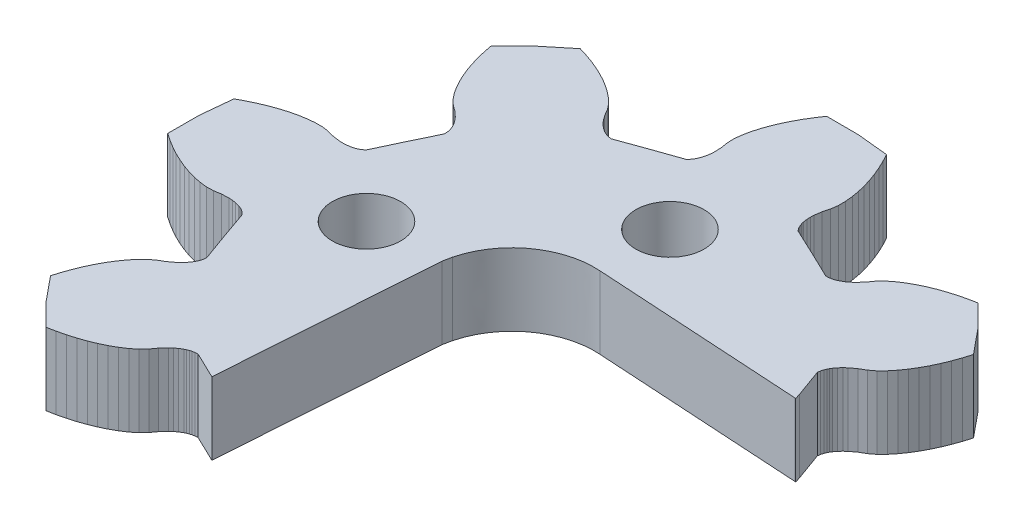
SolidWorks part; units mm, degrees
ref_plane "Front Plane" through (0, 0, 0) normal (0, 0, 1) x (1, 0, 0)
ref_plane "Top Plane" through (0, 0, 0) normal (0, 1, 0) x (1, 0, 0)
ref_plane "Right Plane" through (0, 0, 0) normal (1, 0, 0) x (0, 0, -1)
sketch "Sketch1" plane through (0, 0, 0) normal (0, 1, 0) x (1, 0, 0)
  line L641 (158.2055, 184.3782) -> (158.2815, 184.7575)
  line L1031 (158.2055, 184.3782) -> (157.5478, 174.9321)
  line L1032 (157.5478, 174.9321) -> (156.3907, 175.4893)
  line L1033 (156.3907, 175.4893) -> (156.2563, 175.4858)
  line L1034 (156.2563, 175.4858) -> (156.1474, 175.4663)
  line L1035 (156.1474, 175.4663) -> (156.0523, 175.4384)
  line L1036 (156.0523, 175.4384) -> (155.9664, 175.4045)
  line L1037 (155.9664, 175.4045) -> (155.887, 175.3665)
  line L1038 (155.887, 175.3665) -> (155.7433, 175.2801)
  line L1039 (155.7433, 175.2801) -> (155.6145, 175.184)
  line L1040 (155.6145, 175.184) -> (155.4971, 175.0797)
  line L1041 (155.4971, 175.0797) -> (155.2891, 174.8525)
  line L1042 (155.2891, 174.8525) -> (155.1096, 174.6047)
  line L1043 (155.1096, 174.6047) -> (154.8991, 174.3794)
  line L1044 (154.8991, 174.3794) -> (154.6507, 174.1822)
  line L1045 (154.6507, 174.1822) -> (154.3788, 174.0031)
  line L1046 (154.3788, 174.0031) -> (154.0875, 173.8402)
  line L1047 (154.0875, 173.8402) -> (153.7792, 173.6924)
  line L1048 (153.7792, 173.6924) -> (153.4552, 173.5595)
  line L1049 (153.4552, 173.5595) -> (153.1171, 173.4413)
  line L1050 (153.1171, 173.4413) -> (152.7655, 173.3379)
  line L1051 (152.7655, 173.3379) -> (152.4015, 173.2492)
  line L1052 (152.4015, 173.2492) -> (152.0259, 173.1755)
  line L1053 (152.0259, 173.1755) -> (151.048, 174.159)
  line L1054 (151.048, 174.159) -> (150.169, 175.2315)
  line L1055 (150.169, 175.2315) -> (150.2803, 175.5978)
  line L1056 (150.2803, 175.5978) -> (150.4055, 175.9509)
  line L1057 (150.4055, 175.9509) -> (150.5442, 176.2901)
  line L1058 (150.5442, 176.2901) -> (150.6962, 176.6146)
  line L1059 (150.6962, 176.6146) -> (150.8613, 176.9233)
  line L1060 (150.8613, 176.9233) -> (151.0396, 177.215)
  line L1061 (151.0396, 177.215) -> (151.2311, 177.4883)
  line L1062 (151.2311, 177.4883) -> (151.437, 177.7405)
  line L1063 (151.437, 177.7405) -> (151.6583, 177.9678)
  line L1064 (151.6583, 177.9678) -> (151.9039, 178.1542)
  line L1065 (151.9039, 178.1542) -> (152.1686, 178.3078)
  line L1066 (152.1686, 178.3078) -> (152.4158, 178.4915)
  line L1067 (152.4158, 178.4915) -> (152.5313, 178.5978)
  line L1068 (152.5313, 178.5978) -> (152.6402, 178.7161)
  line L1069 (152.6402, 178.7161) -> (152.7405, 178.8504)
  line L1070 (152.7405, 178.8504) -> (152.7865, 178.9253)
  line L1071 (152.7865, 178.9253) -> (152.829, 179.0074)
  line L1072 (152.829, 179.0074) -> (152.8665, 179.0992)
  line L1073 (152.8665, 179.0992) -> (152.8967, 179.2055)
  line L1074 (152.8967, 179.2055) -> (152.9139, 179.339)
  line L1075 (152.9139, 179.339) -> (152.4773, 180.5465)
  line L1076 (152.4773, 180.5465) -> (152.0529, 181.7587)
  line L1077 (152.0529, 181.7587) -> (151.9553, 181.8512)
  line L1078 (151.9553, 181.8512) -> (151.8647, 181.9145)
  line L1079 (151.8647, 181.9145) -> (151.7777, 181.962)
  line L1080 (151.7777, 181.962) -> (151.693, 181.9989)
  line L1081 (151.693, 181.9989) -> (151.6099, 182.0279)
  line L1082 (151.6099, 182.0279) -> (151.4474, 182.0686)
  line L1083 (151.4474, 182.0686) -> (151.2881, 182.0916)
  line L1084 (151.2881, 182.0916) -> (151.1315, 182.1009)
  line L1085 (151.1315, 182.1009) -> (150.8238, 182.0873)
  line L1086 (150.8238, 182.0873) -> (150.5216, 182.0391)
  line L1087 (150.5216, 182.0391) -> (150.2134, 182.0285)
  line L1088 (150.2134, 182.0285) -> (149.8983, 182.0648)
  line L1089 (149.8983, 182.0648) -> (149.5794, 182.1305)
  line L1090 (149.5794, 182.1305) -> (149.2582, 182.2212)
  line L1091 (149.2582, 182.2212) -> (148.9358, 182.3348)
  line L1092 (148.9358, 182.3348) -> (148.6128, 182.4697)
  line L1093 (148.6128, 182.4697) -> (148.29, 182.6254)
  line L1094 (148.29, 182.6254) -> (147.9683, 182.8007)
  line L1095 (147.9683, 182.8007) -> (147.6481, 182.9954)
  line L1096 (147.6481, 182.9954) -> (147.3305, 183.209)
  line L1097 (147.3305, 183.209) -> (147.3344, 184.5957)
  line L1098 (147.3344, 184.5957) -> (147.4712, 185.9759)
  line L1099 (147.4712, 185.9759) -> (147.8091, 186.156)
  line L1100 (147.8091, 186.156) -> (148.1472, 186.3172)
  line L1101 (148.1472, 186.3172) -> (148.4852, 186.4591)
  line L1102 (148.4852, 186.4591) -> (148.822, 186.581)
  line L1103 (148.822, 186.581) -> (149.1571, 186.6825)
  line L1104 (149.1571, 186.6825) -> (149.4895, 186.7628)
  line L1105 (149.4895, 186.7628) -> (149.8181, 186.8205)
  line L1106 (149.8181, 186.8205) -> (150.142, 186.8534)
  line L1107 (150.142, 186.8534) -> (150.4592, 186.8575)
  line L1108 (150.4592, 186.8575) -> (150.7647, 186.8157)
  line L1109 (150.7647, 186.8157) -> (151.0604, 186.7369)
  line L1110 (151.0604, 186.7369) -> (151.3652, 186.6922)
  line L1111 (151.3652, 186.6922) -> (151.5219, 186.6856)
  line L1112 (151.5219, 186.6856) -> (151.6826, 186.6924)
  line L1113 (151.6826, 186.6924) -> (151.8485, 186.7163)
  line L1114 (151.8485, 186.7163) -> (151.9341, 186.7368)
  line L1115 (151.9341, 186.7368) -> (152.022, 186.765)
  line L1116 (152.022, 186.765) -> (152.1135, 186.8033)
  line L1117 (152.1135, 186.8033) -> (152.2101, 186.8571)
  line L1118 (152.2101, 186.8571) -> (152.3166, 186.9392)
  line L1119 (152.3166, 186.9392) -> (152.8617, 188.102)
  line L1120 (152.8617, 188.102) -> (153.4187, 189.2591)
  line L1121 (153.4187, 189.2591) -> (153.4151, 189.3934)
  line L1122 (153.4151, 189.3934) -> (153.3959, 189.5023)
  line L1123 (153.3959, 189.5023) -> (153.3679, 189.5974)
  line L1124 (153.3679, 189.5974) -> (153.3341, 189.6834)
  line L1125 (153.3341, 189.6834) -> (153.2959, 189.7627)
  line L1126 (153.2959, 189.7627) -> (153.2097, 189.9064)
  line L1127 (153.2097, 189.9064) -> (153.1135, 190.0352)
  line L1128 (153.1135, 190.0352) -> (153.0093, 190.1526)
  line L1129 (153.0093, 190.1526) -> (152.782, 190.3606)
  line L1130 (152.782, 190.3606) -> (152.5343, 190.5402)
  line L1131 (152.5343, 190.5402) -> (152.3089, 190.7506)
  line L1132 (152.3089, 190.7506) -> (152.1117, 190.9991)
  line L1133 (152.1117, 190.9991) -> (151.9326, 191.271)
  line L1134 (151.9326, 191.271) -> (151.7697, 191.5622)
  line L1135 (151.7697, 191.5622) -> (151.622, 191.8705)
  line L1136 (151.622, 191.8705) -> (151.489, 192.1945)
  line L1137 (151.489, 192.1945) -> (151.3709, 192.5328)
  line L1138 (151.3709, 192.5328) -> (151.2672, 192.8842)
  line L1139 (151.2672, 192.8842) -> (151.1786, 193.2482)
  line L1140 (151.1786, 193.2482) -> (151.105, 193.6238)
  line L1141 (151.105, 193.6238) -> (152.0885, 194.6016)
  line L1142 (152.0885, 194.6016) -> (153.1611, 195.4808)
  line L1143 (153.1611, 195.4808) -> (153.5274, 195.3694)
  line L1144 (153.5274, 195.3694) -> (153.8804, 195.2442)
  line L1145 (153.8804, 195.2442) -> (154.2196, 195.1056)
  line L1146 (154.2196, 195.1056) -> (154.544, 194.9535)
  line L1147 (154.544, 194.9535) -> (154.8528, 194.7885)
  line L1148 (154.8528, 194.7885) -> (155.1446, 194.6102)
  line L1149 (155.1446, 194.6102) -> (155.4178, 194.4185)
  line L1150 (155.4178, 194.4185) -> (155.6701, 194.2128)
  line L1151 (155.6701, 194.2128) -> (155.8972, 193.9915)
  line L1152 (155.8972, 193.9915) -> (156.0838, 193.7458)
  line L1153 (156.0838, 193.7458) -> (156.2372, 193.4811)
  line L1154 (156.2372, 193.4811) -> (156.421, 193.2338)
  line L1155 (156.421, 193.2338) -> (156.5273, 193.1183)
  line L1156 (156.5273, 193.1183) -> (156.6456, 193.0096)
  line L1157 (156.6456, 193.0096) -> (156.7798, 192.9091)
  line L1158 (156.7798, 192.9091) -> (156.8549, 192.8632)
  line L1159 (156.8549, 192.8632) -> (156.9369, 192.8208)
  line L1160 (156.9369, 192.8208) -> (157.0287, 192.7833)
  line L1161 (157.0287, 192.7833) -> (157.1351, 192.7529)
  line L1162 (157.1351, 192.7529) -> (157.2684, 192.7357)
  line L1163 (157.2684, 192.7357) -> (158.4761, 193.1725)
  line L1164 (158.4761, 193.1725) -> (159.6882, 193.5968)
  line L1165 (159.6882, 193.5968) -> (159.7808, 193.6943)
  line L1166 (159.7808, 193.6943) -> (159.8439, 193.785)
  line L1167 (159.8439, 193.785) -> (159.8915, 193.8721)
  line L1168 (159.8915, 193.8721) -> (159.9284, 193.9568)
  line L1169 (159.9284, 193.9568) -> (159.9576, 194.0398)
  line L1170 (159.9576, 194.0398) -> (159.9981, 194.2024)
  line L1171 (159.9981, 194.2024) -> (160.0212, 194.3615)
  line L1172 (160.0212, 194.3615) -> (160.0305, 194.5182)
  line L1173 (160.0305, 194.5182) -> (160.0168, 194.826)
  line L1174 (160.0168, 194.826) -> (159.9686, 195.1281)
  line L1175 (159.9686, 195.1281) -> (159.958, 195.4364)
  line L1176 (159.958, 195.4364) -> (159.9944, 195.7514)
  line L1177 (159.9944, 195.7514) -> (160.06, 196.0703)
  line L1178 (160.06, 196.0703) -> (160.1506, 196.3915)
  line L1179 (160.1506, 196.3915) -> (160.2643, 196.7139)
  line L1180 (160.2643, 196.7139) -> (160.3993, 197.037)
  line L1181 (160.3993, 197.037) -> (160.5548, 197.3597)
  line L1182 (160.5548, 197.3597) -> (160.7302, 197.6815)
  line L1183 (160.7302, 197.6815) -> (160.9249, 198.0016)
  line L1184 (160.9249, 198.0016) -> (161.1385, 198.3193)
  line L1185 (161.1385, 198.3193) -> (162.5253, 198.3152)
  line L1186 (162.5253, 198.3152) -> (163.9054, 198.1784)
  line L1187 (163.9054, 198.1784) -> (164.0856, 197.8407)
  line L1188 (164.0856, 197.8407) -> (164.2467, 197.5026)
  line L1189 (164.2467, 197.5026) -> (164.3885, 197.1647)
  line L1190 (164.3885, 197.1647) -> (164.5105, 196.8278)
  line L1191 (164.5105, 196.8278) -> (164.6121, 196.4927)
  line L1192 (164.6121, 196.4927) -> (164.6923, 196.1603)
  line L1193 (164.6923, 196.1603) -> (164.7499, 195.8316)
  line L1194 (164.7499, 195.8316) -> (164.7829, 195.5078)
  line L1195 (164.7829, 195.5078) -> (164.787, 195.1906)
  line L1196 (164.787, 195.1906) -> (164.7452, 194.8851)
  line L1197 (164.7452, 194.8851) -> (164.6665, 194.5893)
  line L1198 (164.6665, 194.5893) -> (164.6217, 194.2845)
  line L1199 (164.6217, 194.2845) -> (164.6152, 194.1276)
  line L1200 (164.6152, 194.1276) -> (164.6218, 193.9671)
  line L1201 (164.6218, 193.9671) -> (164.6459, 193.8012)
  line L1202 (164.6459, 193.8012) -> (164.6664, 193.7156)
  line L1203 (164.6664, 193.7156) -> (164.6945, 193.6276)
  line L1204 (164.6945, 193.6276) -> (164.7329, 193.5362)
  line L1205 (164.7329, 193.5362) -> (164.7866, 193.4396)
  line L1206 (164.7866, 193.4396) -> (164.8686, 193.3331)
  line L1207 (164.8686, 193.3331) -> (166.0314, 192.7879)
  line L1208 (166.0314, 192.7879) -> (167.1885, 192.2308)
  line L1209 (167.1885, 192.2308) -> (167.323, 192.2345)
  line L1210 (167.323, 192.2345) -> (167.4319, 192.2539)
  line L1211 (167.4319, 192.2539) -> (167.527, 192.2818)
  line L1212 (167.527, 192.2818) -> (167.613, 192.3157)
  line L1213 (167.613, 192.3157) -> (167.6923, 192.3538)
  line L1214 (167.6923, 192.3538) -> (167.8359, 192.44)
  line L1215 (167.8359, 192.44) -> (167.9647, 192.5362)
  line L1216 (167.9647, 192.5362) -> (168.0821, 192.6405)
  line L1217 (168.0821, 192.6405) -> (168.2901, 192.8676)
  line L1218 (168.2901, 192.8676) -> (168.4695, 193.1155)
  line L1219 (168.4695, 193.1155) -> (168.6801, 193.3408)
  line L1220 (168.6801, 193.3408) -> (168.9287, 193.5381)
  line L1221 (168.9287, 193.5381) -> (169.2006, 193.7171)
  line L1222 (169.2006, 193.7171) -> (169.4918, 193.88)
  line L1223 (169.4918, 193.88) -> (169.8001, 194.0277)
  line L1224 (169.8001, 194.0277) -> (170.124, 194.1607)
  line L1225 (170.124, 194.1607) -> (170.4622, 194.2789)
  line L1226 (170.4622, 194.2789) -> (170.8138, 194.3824)
  line L1227 (170.8138, 194.3824) -> (171.1777, 194.4711)
  line L1228 (171.1777, 194.4711) -> (171.5534, 194.5448)
  line L1229 (171.5534, 194.5448) -> (172.5312, 193.5612)
  line L1230 (172.5312, 193.5612) -> (173.4103, 192.4887)
  line L1231 (173.4103, 192.4887) -> (173.2988, 192.1224)
  line L1232 (173.2988, 192.1224) -> (173.1738, 191.7693)
  line L1233 (173.1738, 191.7693) -> (173.035, 191.4301)
  line L1234 (173.035, 191.4301) -> (172.8831, 191.1055)
  line L1235 (172.8831, 191.1055) -> (172.7179, 190.7969)
  line L1236 (172.7179, 190.7969) -> (172.5398, 190.5051)
  line L1237 (172.5398, 190.5051) -> (172.348, 190.2319)
  line L1238 (172.348, 190.2319) -> (172.1423, 189.9797)
  line L1239 (172.1423, 189.9797) -> (171.9209, 189.7524)
  line L1240 (171.9209, 189.7524) -> (171.6753, 189.566)
  line L1241 (171.6753, 189.566) -> (171.4106, 189.4125)
  line L1242 (171.4106, 189.4125) -> (171.1635, 189.2287)
  line L1243 (171.1635, 189.2287) -> (171.0478, 189.1225)
  line L1244 (171.0478, 189.1225) -> (170.939, 189.004)
  line L1245 (170.939, 189.004) -> (170.8387, 188.8699)
  line L1246 (170.8387, 188.8699) -> (170.7927, 188.7948)
  line L1247 (170.7927, 188.7948) -> (170.7504, 188.7129)
  line L1248 (170.7504, 188.7129) -> (170.7129, 188.621)
  line L1249 (170.7129, 188.621) -> (170.6824, 188.5147)
  line L1250 (170.6824, 188.5147) -> (170.6653, 188.3813)
  line L1251 (170.6653, 188.3813) -> (171.1021, 187.1736)
  line L1252 (171.1021, 187.1736) -> (171.1808, 186.9201)
  line L1253 (171.1808, 186.9201) -> (171.1477, 186.9201)
  line L1254 (171.1477, 186.9201) -> (162.0293, 187.4738)
  circle A0 centre (155.0314, 184.2329) radius 1.4998
  circle A1 centre (161.9982, 190.5831) radius 1.4998
  spline S1377 degree 3 poles (162.0293, 187.4738) (160.3215, 187.5891) (158.7208, 186.4754) (158.2815, 184.7575) knots 0.222652 0.222652 0.222652 0.222652 0.4 0.4 0.4 0.4
extrude "Boss-Extrude1" add sketch "Sketch1" along normal blind 3.175
